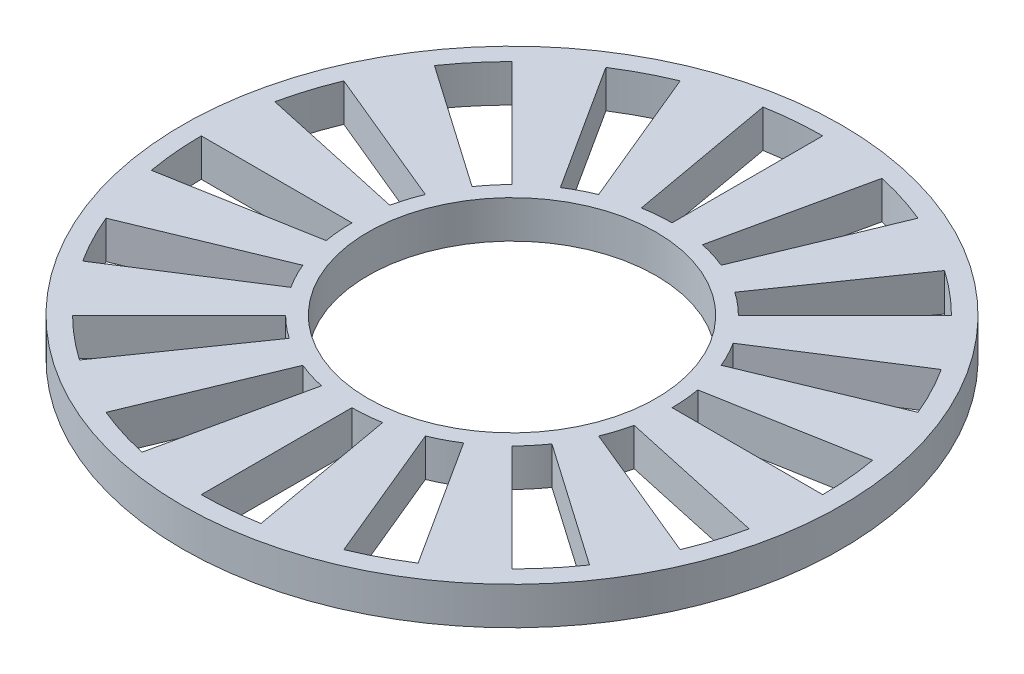
SolidWorks part; units mm, degrees
ref_plane "Front Plane" through (0, 0, 0) normal (0, 0, 1) x (1, 0, 0)
ref_plane "Top Plane" through (0, 0, 0) normal (0, 1, 0) x (1, 0, 0)
ref_plane "Right Plane" through (0, 0, 0) normal (1, 0, 0) x (0, 0, -1)
sketch "Sketch3" plane through (0, 0, 0) normal (0, 1, 0) x (1, 0, 0)
  circle A0 centre (0, 0) radius 17.5
  circle A1 centre (0, 0) radius 7.65
  dimension "D1" = 35
  dimension "D2" = 15.3
extrude "Boss-Extrude2" add sketch "Sketch3" along normal blind 2
sketch "Sketch4" plane through (0, 2, 0) normal (0, 1, 0) x (1, 0, 0)
  line L0 (1.5, -8.3666) -> (2.9118, -16.241)
  line L1 (0, -16.5) -> (0, -8.5)
  line L2 (0, -8.5) -> (0, 0) construction
  line L3 (1.5, -8.3666) -> (0, 0) construction
  arc A0 (0, -8.5) -> (1.5, -8.3666) centre (0, 0) ccw
  arc A1 (0, -16.5) -> (2.9118, -16.241) centre (0, 0) ccw
  dimension "D1" = 16.5
  dimension "D2" = 8.5
  dimension "D3" = 8
  dimension "D4" = 1.5
extrude "Cut-Extrude1" cut sketch "Sketch4" against normal blind 10
pattern_circular "CirPattern1" count 16 over 360 about axis through (0, 0, 0) along (0, 1, 0) of "Cut-Extrude1"
